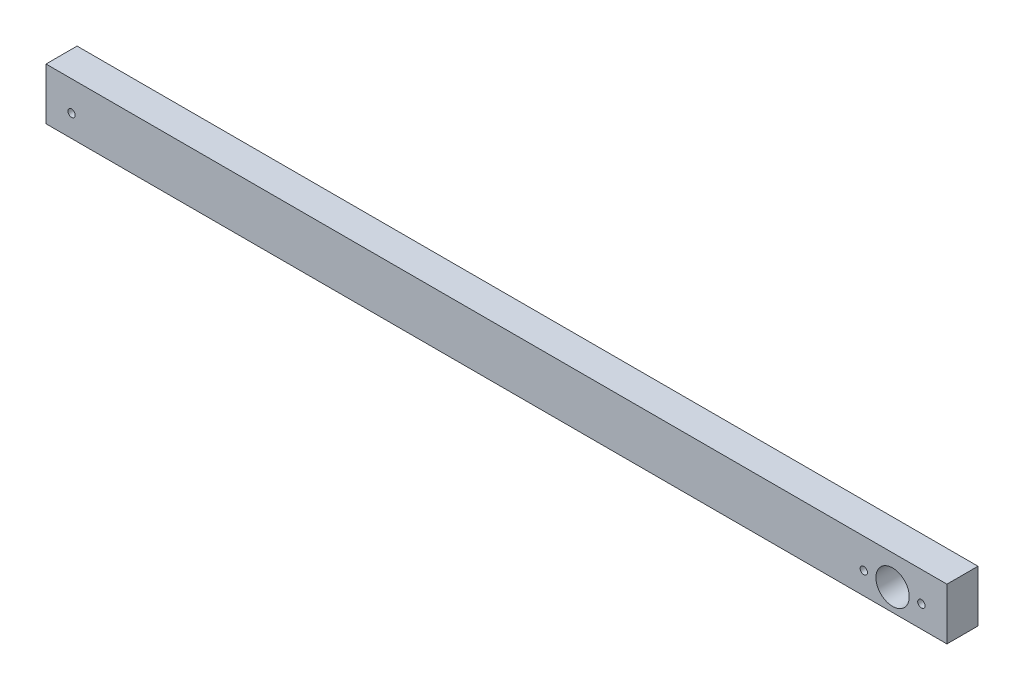
SolidWorks part; units mm, degrees
material "Pine"
ref_plane "Front Plane" through (0, 0, 0) normal (0, 0, 1) x (1, 0, 0)
ref_plane "Top Plane" through (0, 0, 0) normal (0, 1, 0) x (1, 0, 0)
ref_plane "Right Plane" through (0, 0, 0) normal (1, 0, 0) x (0, 0, -1)
sketch "Sketch1" plane through (0, 0, 0) normal (0, 1, 0) x (1, 0, 0)
  line L1 (-276.225, -9.525) -> (276.225, -9.525)
  line L2 (-276.225, -9.525) -> (-276.225, 9.525)
  line L3 (-276.225, 9.525) -> (276.225, 9.525)
  line L4 (276.225, -9.525) -> (276.225, 9.525)
  line L5 (-276.225, -9.525) -> (276.225, 9.525) construction
  line L6 (-276.225, 9.525) -> (276.225, -9.525) construction
  point P0 (0, 0)
  dimension "D1" = 19.05
  dimension "D2" = 552.45
extrude "Boss-Extrude1" add sketch "Sketch1" along normal blind 31.75
sketch "Sketch2" plane through (0, 0, -9.525) normal (0, 0, -1) x (-1, 0, 0)
  circle A1 centre (-242.8875, 13.4937) radius 9.2075 construction
  circle A3 centre (-242.8875, 13.4937) radius 10.2235
  dimension "D3" = 18.415
  dimension "D1" = 242.8875
  dimension "D2" = 13.4937
  dimension "D4" = 1.016
extrude "Cut-Extrude1" cut sketch "Sketch2" against normal through all
sketch "Sketch4" plane through (0, 0, 9.525) normal (0, 0, 1) x (1, 0, 0)
  circle A0 centre (225.2281, 13.4937) radius 2.0193 construction
  circle A1 centre (260.5469, 13.4937) radius 2.0193 construction
  circle A2 centre (225.2281, 13.4937) radius 2.0193
  circle A3 centre (260.5469, 13.4937) radius 2.0193
hole_wizard "CSK for #8 Flat Head Socket Cap Screw1" positions "Sketch5" profile "Sketch6" countersink size "#8" standard "ANSI Inch" end condition through all
sketch "Sketch5" plane through (0, 0, -9.525) normal (0, 0, 1) x (1, 0, 0)
  line L0 (0, 31.75) -> (0, 0) construction
  line L1 (276.225, 31.75) -> (-276.225, 31.75) construction
  point P0 (260.5469, 13.4937)
  point P3 (225.2281, 13.4937)
  point P13 (0, 0)
sketch "Sketch6" plane through (260.5469, 13.4937, -9.525) normal (1, 0, 0) x (0, 1, 0)
  line L0 (0, 0) -> (0, 19.05)
  line L1 (0, 19.05) -> (2.2479, 19.05)
  line L2 (2.2479, 19.05) -> (2.2479, 2.659)
  line L3 (2.2479, 2.659) -> (4.5593, 0)
  line L5 (4.5593, 0) -> (0, 0)
  line L6 (-2.2479, 2.659) -> (-4.5593, 0) construction
  line L11 (0, -6.35) -> (0, 107.95) construction
  dimension "Thru Hole Dia." = 4.4958
  dimension "Thru Hole Depth" = 19.05
  dimension "Near C'Sink Dia." = 9.1186
  dimension "Near C'Sink Angle" = 82
hole_wizard "CSK for #8 Flat Head Machine Screw1" positions "Sketch7" profile "Sketch8" countersink size "#8" standard "ANSI Inch" end condition through all
sketch "Sketch7" plane through (0, 0, -9.525) normal (0, 0, -1) x (-1, 0, 0)
  line L0 (260.5469, 13.4937) -> (-260.5469, 13.4937) construction
  point P0 (260.5469, 13.4937)
  point P90 (-260.5469, 13.4937)
  point P92 (247.5163, 13.0428)
  point P93 (0, 0)
  point P94 (0, 13.4937)
sketch "Sketch8" plane through (-260.5469, 13.4937, -9.525) normal (1, 0, 0) x (0, 1, 0)
  line L0 (0, 0) -> (0, 19.05)
  line L1 (0, 19.05) -> (2.2479, 19.05)
  line L2 (2.2479, 19.05) -> (2.2479, 2.2645)
  line L3 (2.2479, 2.2645) -> (4.2164, 0)
  line L5 (4.2164, 0) -> (0, 0)
  line L6 (-2.2479, 2.2645) -> (-4.2164, 0) construction
  line L11 (0, -6.35) -> (0, 107.95) construction
  dimension "Thru Hole Dia." = 4.4958
  dimension "Thru Hole Depth" = 19.05
  dimension "Near C'Sink Dia." = 8.4328
  dimension "Near C'Sink Angle" = 82
